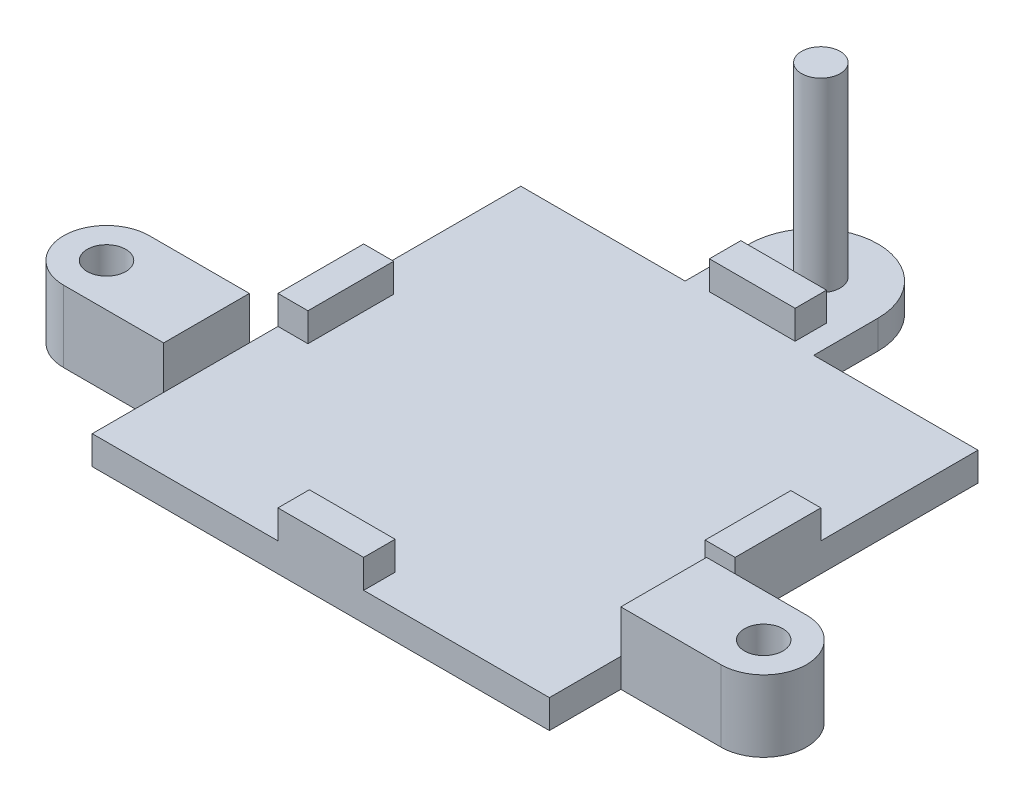
SolidWorks part; units mm, degrees
ref_plane "Front Plane" through (0, 0, 0) normal (0, 0, 1) x (1, 0, 0)
ref_plane "Top Plane" through (0, 0, 0) normal (0, 1, 0) x (1, 0, 0)
ref_plane "Right Plane" through (0, 0, 0) normal (1, 0, 0) x (0, 0, -1)
sketch "Sketch1" plane through (0, 0, 0) normal (0, 1, 0) x (1, 0, 0)
  line L6 (-15.5, 30) -> (-15.5, 11)
  line L7 (-15.5, 11) -> (-22.5, 11)
  line L8 (-15.5, 30) -> (-4, 30)
  line L9 (-4, 30) -> (-4, 34.5)
  line L10 (5, 34.5) -> (5, 30)
  line L11 (5, 30) -> (16.5, 30)
  line L12 (16.5, 30) -> (16.5, 11)
  line L13 (16.5, 11) -> (23.5, 11)
  line L14 (23.5, 5) -> (16.5, 5)
  line L15 (16.5, 5) -> (16.5, 0)
  line L16 (-44.2539, 0) -> (44.2539, 0) construction
  line L17 (16.5, 0) -> (-15.5, 0)
  line L18 (-15.5, 0) -> (-15.5, 5)
  line L19 (-15.5, 5) -> (-22.5, 5)
  line L20 (0, -44.7868) -> (0, 44.7868) construction
  arc A0 (-22.5, 5) -> (-22.5, 11) centre (-22.5, 8) cw
  arc A1 (-4, 34.5) -> (5, 34.5) centre (0.5, 34.5) cw
  arc A2 (23.5, 11) -> (23.5, 5) centre (23.5, 8) cw
  circle A3 centre (-22.5, 8) radius 1.35
  circle A4 centre (23.5, 8) radius 1.35
  point P22 (0.5, 39)
  dimension "D1" = 15.5
  dimension "D6" = 4.5
  dimension "D8" = 46
  dimension "D10" = 3
  dimension "D11" = 2.7
  dimension "D2" = 32
  dimension "D3" = 32
  dimension "D4" = 19
  dimension "D5" = 9
  dimension "D7" = 30
  dimension "D9" = 7
extrude "Boss-Extrude2" add sketch "Sketch1" along normal blind 2
sketch "Sketch3" plane through (0, 2, 0) normal (0, 1, 0) x (1, 0, 0)
  line L0 (-4, 30) -> (-15.5, 30) construction
  line L1 (5, 30) -> (5, 34.5) construction
  circle A0 centre (0.5, 35) radius 1.35
  dimension "D1" = 5
  dimension "D2" = 2.7
  dimension "D3" = 4.5
extrude "Boss-Extrude3" add sketch "Sketch3" along normal blind 13
sketch "Sketch5" plane through (0, 2, 0) normal (0, 1, 0) x (1, 0, 0)
  line L0 (-15.5, 11) -> (-15.5, 5)
  line L1 (16.5, 11) -> (16.5, 5)
  line M4 (-15.5, 11) -> (-22.5, 11)
  arc M5 (-22.5, 11) -> (-22.5, 5) centre (-22.5, 8) ccw
  line M6 (-22.5, 5) -> (-15.5, 5)
  line M10 (16.5, 5) -> (23.5, 5)
  arc M11 (23.5, 5) -> (23.5, 11) centre (23.5, 8) ccw
  line M12 (23.5, 11) -> (16.5, 11)
  circle M18 centre (-22.5, 8) radius 1.35
  circle M19 centre (23.5, 8) radius 1.35
extrude "Boss-Extrude4" add sketch "Sketch5" along normal blind 3 contours L0 M4 M5 M6 M18 | L1 M12 M10 M11 M19
sketch "Sketch6" plane through (0, 0, 0) normal (0, 1, 0) x (1, 0, 0)
  line L0 (-44.2539, 0) -> (44.2539, 0) construction
  line L1 (-2.5, 0) -> (3.5, 0)
  line L2 (-2.5, 0) -> (-2.5, 2.2)
  line L3 (-2.5, 2.2) -> (3.5, 2.2)
  line L4 (3.5, 0) -> (3.5, 2.2)
  line L5 (-15.5, 30) -> (-15.5, 11) construction
  line L6 (-15.5, 19) -> (-13.4, 19)
  line L7 (-15.5, 19) -> (-15.5, 13)
  line L8 (-15.5, 13) -> (-13.4, 13)
  line L9 (-13.4, 19) -> (-13.4, 13)
  line L10 (16.5, 11) -> (16.5, 30) construction
  line L11 (16.5, 19) -> (14.4, 19)
  line L12 (16.5, 19) -> (16.5, 13)
  line L13 (16.5, 13) -> (14.4, 13)
  line L14 (14.4, 19) -> (14.4, 13)
  line L15 (-4, 30) -> (-15.5, 30) construction
  line L20 (16.5, 30) -> (5, 30) construction
  line L21 (16.5, 0) -> (16.5, 5) construction
  line L24 (-2.5, 32.4) -> (3.5, 32.4)
  line L25 (-2.5, 32.4) -> (-2.5, 30.2)
  line L26 (-2.5, 30.2) -> (3.5, 30.2)
  line L27 (3.5, 32.4) -> (3.5, 30.2)
  point P26 (3.5, 1.1)
  dimension "D1" = 2.1
  dimension "D2" = 2.1
  dimension "D3" = 6
  dimension "D4" = 6
  dimension "D5" = 11
  dimension "D6" = 11
  dimension "D7" = 6
  dimension "D8" = 2.2
  dimension "D9" = 13
  dimension "D10" = 6
  dimension "D11" = 13
  dimension "D12" = 2.2
  dimension "D13" = 28
extrude "Boss-Extrude5" add sketch "Sketch6" along normal blind 4
equation "\"ScrewDist\"=6"
